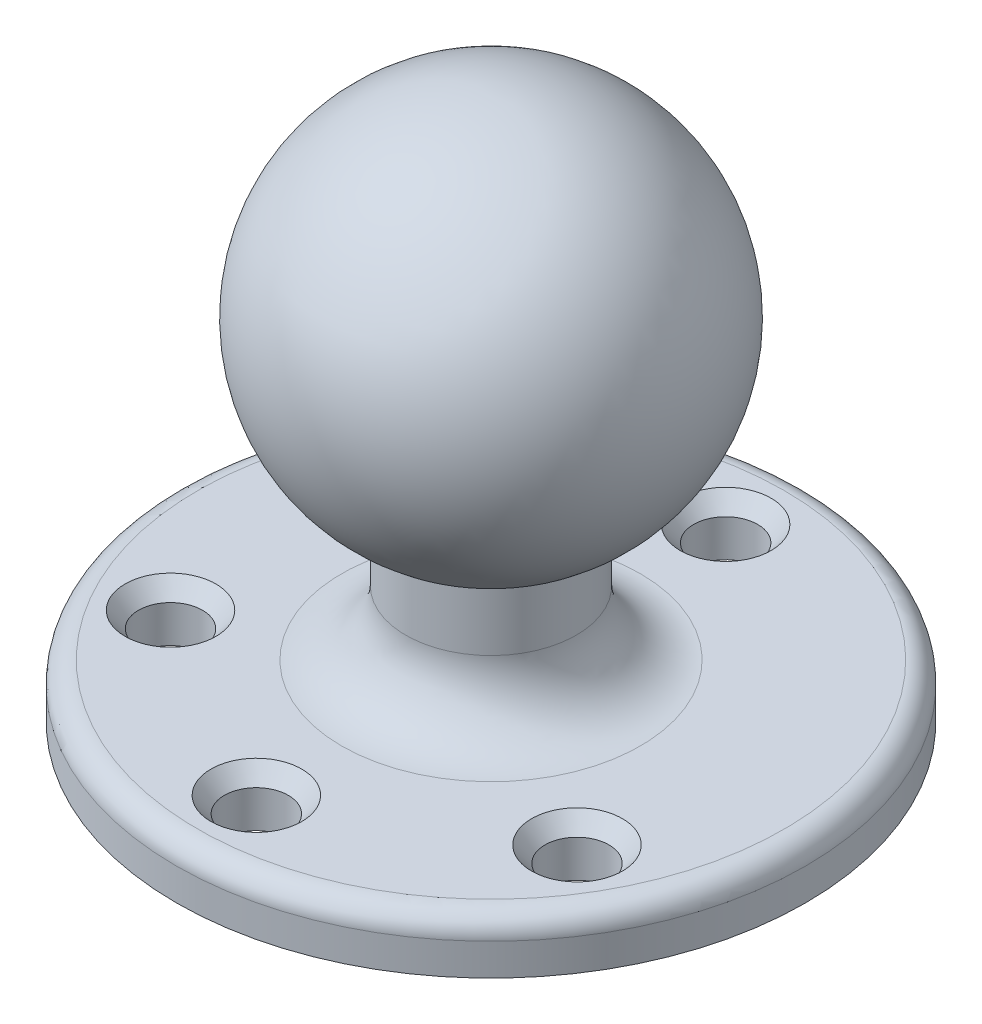
SolidWorks part; units mm, degrees
ref_plane "Front Plane" through (0, 0, 0) normal (0, 0, 1) x (1, 0, 0)
ref_plane "Top Plane" through (0, 0, 0) normal (0, 1, 0) x (1, 0, 0)
ref_plane "Right Plane" through (0, 0, 0) normal (1, 0, 0) x (0, 0, -1)
sketch "Sketch1" plane through (0, 0, 0) normal (1, 0, 0) x (0, 0, -1)
  line L0 (0, 0) -> (46.8249, 0)
  line L1 (46.8249, 0) -> (46.8249, 4.7498)
  line L2 (43.6499, 7.9248) -> (22.225, 7.9248)
  line L3 (12.7, 26.4723) -> (12.7, 17.4498)
  line L4 (0, 0) -> (0, 80.645) construction
  line L5 (0, 0) -> (0, 80.645)
  arc A0 (12.7, 26.4723) -> (0, 80.645) centre (0, 52.07) ccw
  arc A1 (22.225, 7.9248) -> (12.7, 17.4498) centre (22.225, 17.4498) cw
  arc A2 (46.8249, 4.7498) -> (43.6499, 7.9248) centre (43.6499, 4.7498) ccw
  point P15 (46.8249, 7.9248)
  dimension "D3" = 57.15
  dimension "D5" = 9.525
  dimension "D7" = 3.175
  dimension "D1" = 46.8249
  dimension "D2" = 7.9248
  dimension "D4" = 52.07
  dimension "D8" = 12.7
revolve "Revolve1" add sketch "Sketch1" angle 360 about L4
sketch "Sketch3" plane through (0, 0, 0) normal (0, -1, 0) x (1, 0, 0)
  line L0 (-30.2514, 17.4498) -> (30.2514, 17.4498) construction
  line L1 (0, 34.925) -> (0, -34.925) construction
  circle A0 centre (-30.2514, 17.4498) radius 4.7625
  circle A1 centre (30.2514, 17.4498) radius 4.7625
  circle A2 centre (0, -34.925) radius 4.7625
  circle A3 centre (0, 34.925) radius 4.7625
  circle A4 centre (0, 0) radius 34.9234 construction
  point P8 (0, 17.4498)
  point P9 (0, 0)
  dimension "D1" = 69.85
  dimension "D4" = 9.525
  dimension "D2" = 60.5028
  dimension "D3" = 17.4752
extrude "Cut-Extrude1" cut sketch "Sketch3" against normal blind 10
chamfer "Chamfer1" distance 2 angle 50 4 edges at (-30.2514, 7.9248, 22.2123) (0, 7.9248, -30.1625) (30.2514, 7.9248, 22.2123) (0, 7.9248, 39.6875)
